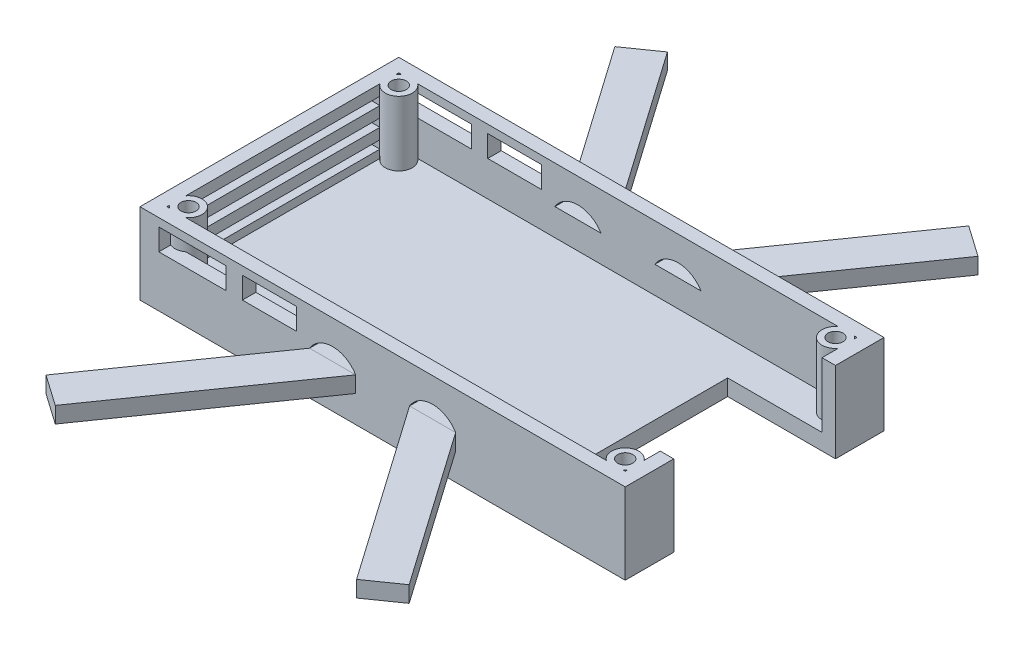
SolidWorks part; units mm, degrees
ref_plane "Přední rovina" through (0, 0, 0) normal (0, 0, 1) x (1, 0, 0)
ref_plane "Horní rovina" through (0, 0, 0) normal (0, 1, 0) x (1, 0, 0)
ref_plane "Pravá rovina" through (0, 0, 0) normal (1, 0, 0) x (0, 0, -1)
sketch "Skica1" plane through (0, 0, 0) normal (0, 1, 0) x (1, 0, 0)
  line L2 (45, 24) -> (45, -24)
  line L3 (45, -24) -> (-45, -24)
  line L4 (-45, -24) -> (-45, 24)
  line L5 (-45, 24) -> (45, 24)
  dimension "D3" = 48
  dimension "D4" = 90
extrude "Přidat vysunutím1" add sketch "Skica1" along normal blind 3
sketch "Skica2" plane through (0, 0, 0) normal (0, 1, 0) x (1, 0, 0)
  line L0 (-33.6771, -52.751) -> (-13.5454, -24)
  line L1 (-45, -24) -> (45, -24) construction
  line L2 (-5, -24) -> (-27.9431, -56.7661)
  line L3 (-13.5454, -24) -> (-11.1039, -24)
  line L4 (5, -24) -> (27.9431, -56.7661)
  line L5 (-27.9431, -56.7661) -> (-33.6771, -52.751)
  line L7 (-11.1039, -24) -> (-5, -24)
  line L8 (27.9431, -56.7661) -> (33.6771, -52.751)
  line L10 (11.1039, -24) -> (5, -24)
  line L11 (33.6771, -52.751) -> (13.5454, -24)
  line L12 (45, 24) -> (-45, 24) construction
  line L13 (-5, 24) -> (-27.9431, 56.7661)
  line L14 (13.5454, -24) -> (11.1039, -24)
  line L15 (5, 24) -> (27.9431, 56.7661)
  line L16 (27.9431, 56.7661) -> (33.6771, 52.751)
  line L19 (-27.9431, 56.7661) -> (-33.6771, 52.751)
  line L21 (-11.1039, 24) -> (-5, 24)
  line L22 (11.1039, 24) -> (5, 24)
  line L23 (33.6771, 52.751) -> (13.5454, 24)
  line L24 (13.5454, 24) -> (11.1039, 24)
  line L25 (-33.6771, 52.751) -> (-13.5454, 24)
  line L26 (-13.5454, 24) -> (-11.1039, 24)
  dimension "D2" = 40
  dimension "D5" = 40
  dimension "D7" = 7
  dimension "D8" = 40
  dimension "D10" = 40
  dimension "D11" = 55
  dimension "D12" = 55
extrude "Přidat vysunutím2" add sketch "Skica2" along normal blind 3 from offset 5
sketch "Skica3" plane through (0, 3, 0) normal (0, 1, 0) x (1, 0, 0)
  line L1 (-45, -24) -> (45, -24)
  line L2 (-45, -24) -> (-45, 24)
  line L3 (-45, 24) -> (45, 24)
  line L4 (45, -24) -> (45, 24)
  line L5 (42.5, 21.5) -> (-42.5, 21.5)
  line L6 (42.5, 21.5) -> (42.5, -21.5)
  line L7 (42.5, -21.5) -> (-42.5, -21.5)
  line L8 (-42.5, 21.5) -> (-42.5, -21.5)
  dimension "D1" = 2.5
  dimension "D2" = 2.5
  dimension "D3" = 2.5
  dimension "D4" = 2.5
extrude "Přidat vysunutím3" add sketch "Skica3" along normal blind 12
sketch "Skica4" plane through (45, 0, 0) normal (1, 0, 0) x (0, 0, -1)
  line L0 (-24, 15) -> (24, 15) construction
  line L1 (-15, 15) -> (15, 15)
  line L2 (-15, 15) -> (-15, 0)
  line L3 (-15, 0) -> (15, 0)
  line L4 (15, 15) -> (15, 0)
  line L5 (-24, 0) -> (24, 0) construction
  line L6 (24, 15) -> (24, 0) construction
  line L7 (-24, 15) -> (-24, 0) construction
  dimension "D1" = 9
  dimension "D2" = 9
extrude "Odebrat vysunutím1" cut sketch "Skica4" against normal blind 20
sketch "Skica10" plane through (0, 0, 24) normal (0, 0, 1) x (1, 0, 0)
  line L0 (-45, 15) -> (-45, 0) construction
  line L1 (-41.5, 13.5) -> (-29, 13.5)
  line L2 (-41.5, 13.5) -> (-41.5, 9.5)
  line L3 (-41.5, 9.5) -> (-29, 9.5)
  line L4 (-29, 13.5) -> (-29, 9.5)
  line L5 (-26, 9.5) -> (-16, 9.5)
  line L6 (-26, 9.5) -> (-26, 13.5)
  line L7 (-26, 13.5) -> (-16, 13.5)
  line L8 (-16, 9.5) -> (-16, 13.5)
  line L9 (-45, 15) -> (45, 15) construction
  dimension "D1" = 4
  dimension "D2" = 12.5
  dimension "D3" = 4
  dimension "D4" = 10
  dimension "D5" = 3.5
  dimension "D6" = 3
  dimension "D7" = 1.5
extrude "Odebrat vysunutím5" cut sketch "Skica10" against normal blind 50
sketch "Skica11" plane through (-45, 0, 0) normal (-1, 0, 0) x (0, 0, 1)
  line L0 (-24, 15) -> (-24, 0) construction
  line L1 (-18, 13) -> (18, 13)
  line L2 (-18, 13) -> (-18, 11.5)
  line L3 (-18, 11.5) -> (18, 11.5)
  line L4 (18, 13) -> (18, 11.5)
  line L5 (24, 15) -> (24, 0) construction
  line L6 (-24, 15) -> (24, 15) construction
  line L8 (-18, 9.5) -> (18, 9.5)
  line L9 (-18, 9.5) -> (-18, 8)
  line L10 (-18, 8) -> (18, 8)
  line L11 (18, 9.5) -> (18, 8)
  line L12 (-18, 6) -> (18, 6)
  line L13 (-18, 6) -> (-18, 4.5)
  line L14 (-18, 4.5) -> (18, 4.5)
  line L15 (18, 6) -> (18, 4.5)
  dimension "D1" = 1.5
  dimension "D2" = 6
  dimension "D3" = 6
  dimension "D4" = 2
  dimension "D5" = 1.5
  dimension "D6" = 36
  dimension "D7" = 2
  dimension "D8" = 1.5
  dimension "D9" = 2
extrude "Odebrat vysunutím6" cut sketch "Skica11" against normal blind 5
sketch "Skica12" plane through (0, 0, 24) normal (0, 0, 1) x (1, 0, 0)
  line L1 (-5, 8) -> (-13.5454, 8)
  line L2 (-27.9431, 8) -> (-5, 8) construction
  line L3 (-5, 8) -> (-5, 5) construction
  line L4 (-5, 8) -> (-13.5454, 8) construction
  line L5 (5, 8) -> (13.5454, 8)
  arc A0 (-13.5454, 8) -> (-5, 8) centre (-9.2727, 5.4031) cw
  arc A1 (5, 8) -> (13.5454, 8) centre (9.2727, 5.4031) cw
  dimension "D1" = 5
  dimension "D2" = 5
extrude "Odebrat vysunutím7" cut sketch "Skica12" against normal blind 50
sketch "Skica14" plane through (0, 3, 0) normal (0, 1, 0) x (1, 0, 0)
  line L7 (-42.5, 21.5) -> (-42.5, -21.5) construction
  circle A0 centre (-40.5, 19.5) radius 1.4
  circle A1 centre (-40.5, 19.5) radius 2.5
  circle A2 centre (-40.5, -19.5) radius 1.4
  circle A3 centre (-40.5, -19.5) radius 2.5
  circle A4 centre (40.5, -19.5) radius 1.4
  circle A5 centre (40.5, -19.5) radius 2.5
  circle A6 centre (40.5, 19.5) radius 1.4
  circle A7 centre (40.5, 19.5) radius 2.5
  dimension "D2" = 2.8
  dimension "D4" = 5
  dimension "D6" = 2.8
  dimension "D7" = 5
  dimension "D5" = 2.8
  dimension "D8" = 5
  dimension "D9" = 2.8
  dimension "D10" = 5
  dimension "D3" = 2
extrude "Přidat vysunutím4" add sketch "Skica14" along normal blind 12
